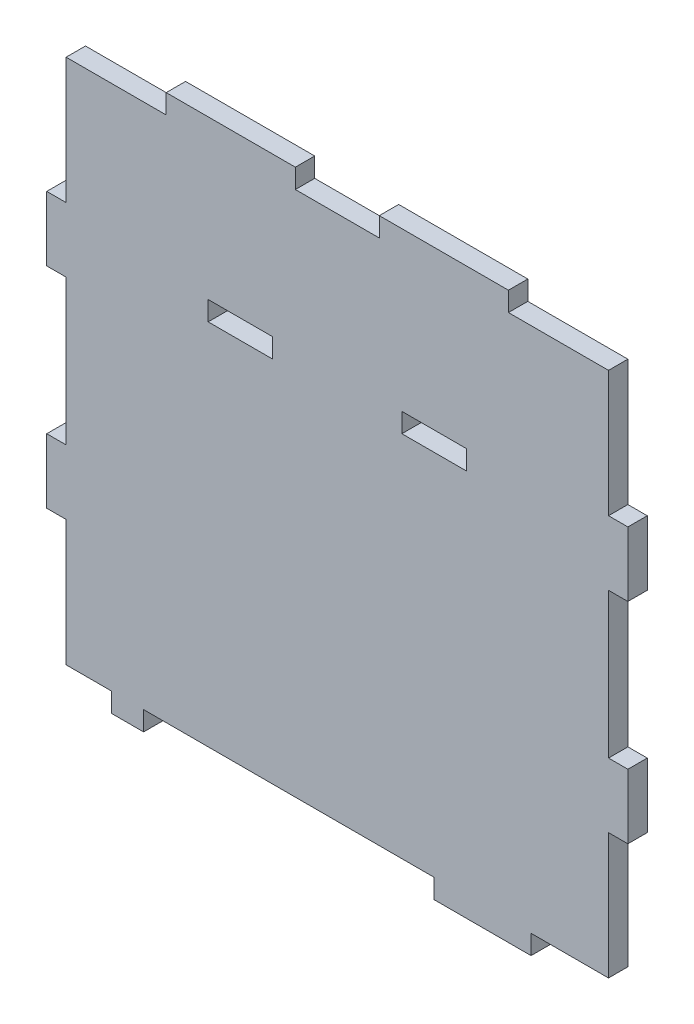
SolidWorks part; units mm, degrees
ref_plane "Plan de face" through (0, 0, 0) normal (0, 0, 1) x (1, 0, 0)
ref_plane "Plan de dessus" through (0, 0, 0) normal (0, 1, 0) x (1, 0, 0)
ref_plane "Plan de droite" through (0, 0, 0) normal (1, 0, 0) x (0, 0, -1)
sketch "Esquisse1" plane through (0, 0, 0) normal (0, 0, 1) x (1, 0, 0)
  line L1 (0, 0) -> (-180, 0)
  line L2 (0, 0) -> (0, 175)
  line L3 (0, 175) -> (-180, 175)
  line L4 (-180, 0) -> (-180, 175)
  dimension "D1" = 175
  dimension "D2" = 180
extrude "Boss.-Extru.1" add sketch "Esquisse1" along normal blind 6
sketch "Esquisse2" plane through (0, 0, 6) normal (0, 0, 1) x (1, 0, 0)
  line L0 (-180, 175) -> (-180, 0) construction
  line L1 (-180, 0) -> (-174, 0)
  line L2 (-180, 0) -> (-180, 45)
  line L3 (-180, 45) -> (-174, 45)
  line L4 (-174, 6) -> (-174, 45)
  line L5 (-180, 65) -> (-174, 65)
  line L6 (-180, 65) -> (-180, 110)
  line L7 (-180, 110) -> (-174, 110)
  line L8 (-174, 65) -> (-174, 110)
  line L10 (-160, 6) -> (-160, 0)
  line L11 (-180, 175) -> (-180, 130)
  line L12 (-180, 130) -> (-174, 130)
  line L13 (-174, 169) -> (-174, 130)
  line L14 (-160, 0) -> (-174, 0)
  line L16 (-160, 6) -> (-174, 6)
  line L18 (0, 0) -> (0, 175) construction
  line L19 (-150, 0) -> (-60, 0)
  line L20 (-150, 0) -> (-150, 6)
  line L21 (-150, 6) -> (-60, 6)
  line L22 (-60, 0) -> (-60, 6)
  line L23 (0, 175) -> (-180, 175) construction
  line L24 (0, 0) -> (-6, 0)
  line L25 (0, 0) -> (0, 45)
  line L26 (0, 45) -> (-6, 45)
  line L27 (-6, 6) -> (-6, 45)
  line L28 (0, 65) -> (-6, 65)
  line L29 (0, 65) -> (0, 110)
  line L30 (0, 110) -> (-6, 110)
  line L31 (-6, 65) -> (-6, 110)
  line L32 (-30, 0) -> (-6, 0)
  line L33 (0, 175) -> (0, 130)
  line L34 (0, 130) -> (-6, 130)
  line L35 (-6, 169) -> (-6, 130)
  line L36 (-180, 175) -> (-143, 175)
  line L37 (-30, 0) -> (-30, 6)
  line L38 (-174, 169) -> (-143, 169)
  line L39 (-143, 175) -> (-143, 169)
  line L40 (-103, 175) -> (-77, 175)
  line L41 (-103, 175) -> (-103, 169)
  line L42 (-103, 169) -> (-77, 169)
  line L43 (-77, 175) -> (-77, 169)
  line L44 (-30, 6) -> (-6, 6)
  line L45 (0, 175) -> (-37, 175)
  line L47 (-6, 169) -> (-37, 169)
  line L48 (-37, 175) -> (-37, 169)
  dimension "D1" = 45
  dimension "D2" = 45
  dimension "D3" = 20
  dimension "D4" = 20
  dimension "D5" = 6
  dimension "D6" = 6
  dimension "D7" = 6
  dimension "D9" = 14
  dimension "D10" = 30
  dimension "D11" = 24
  dimension "D12" = 6
  dimension "D13" = 6
  dimension "D14" = 45
  dimension "D15" = 45
  dimension "D16" = 20
  dimension "D17" = 20
  dimension "D18" = 6
  dimension "D19" = 6
  dimension "D20" = 6
  dimension "D21" = 6
  dimension "D22" = 6
  dimension "D23" = 6
  dimension "D24" = 40
  dimension "D25" = 26
  dimension "D26" = 40
  dimension "D27" = 6
extrude "Enlèv. mat encoche" cut sketch "Esquisse2" against normal through all
sketch "Esquisse3" plane through (0, 0, 6) normal (0, 0, 1) x (1, 0, 0)
  line L0 (-180, 130) -> (-180, 110) construction
  line L1 (-130, 126) -> (-110, 126)
  line L2 (-130, 126) -> (-130, 120)
  line L3 (-130, 120) -> (-110, 120)
  line L4 (-110, 126) -> (-110, 120)
  line L5 (-70, 126) -> (-50, 126)
  line L6 (-70, 126) -> (-70, 120)
  line L7 (-70, 120) -> (-50, 120)
  line L8 (-50, 126) -> (-50, 120)
  line L9 (-103, 175) -> (-143, 175) construction
  line L10 (-37, 175) -> (-77, 175) construction
  dimension "D1" = 20
  dimension "D2" = 20
  dimension "D3" = 40
  dimension "D4" = 50
  dimension "D5" = 49
  dimension "D6" = 6
  dimension "D7" = 6
  dimension "D8" = 49
extrude "Enlèv. mat encoche etage" cut sketch "Esquisse3" against normal through all
